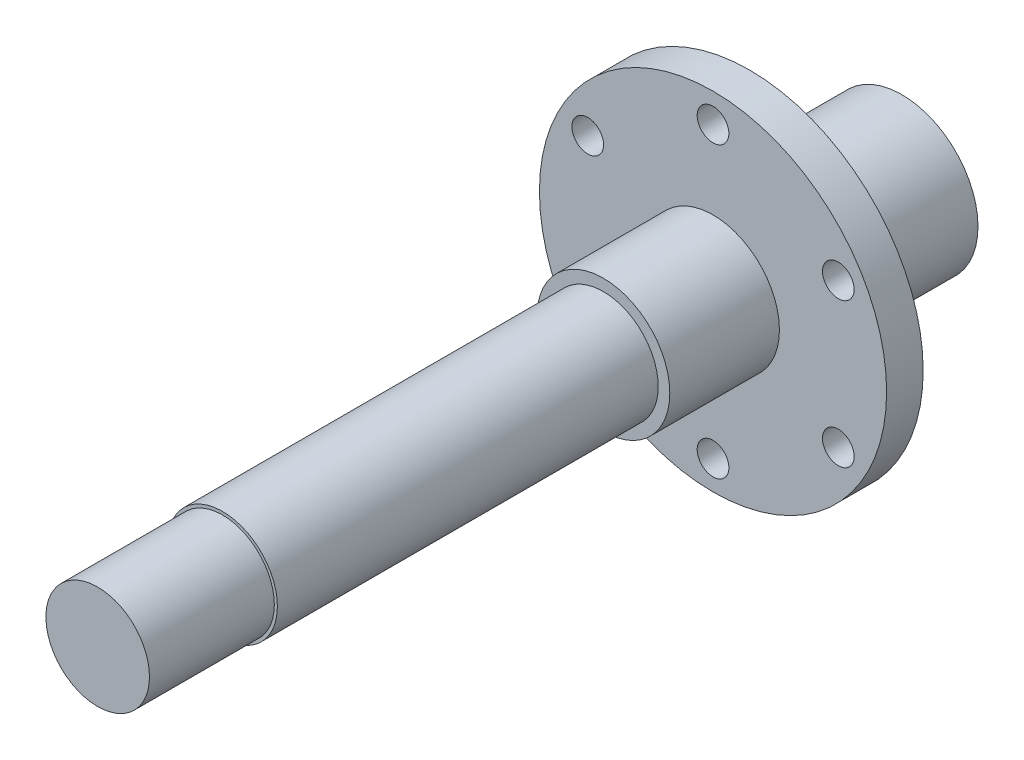
SolidWorks part; units mm, degrees
material "Galvanized Steel"
ref_plane "Front Plane" through (0, 0, 0) normal (0, 0, 1) x (1, 0, 0)
ref_plane "Top Plane" through (0, 0, 0) normal (0, 1, 0) x (1, 0, 0)
ref_plane "Right Plane" through (0, 0, 0) normal (1, 0, 0) x (0, 0, -1)
sketch "Sketch1" plane through (0, 0, 0) normal (0, 0, 1) x (1, 0, 0)
  circle A0 centre (0, 0) radius 12.5
  dimension "D1" = 25
extrude "Boss-Extrude1" add sketch "Sketch1" along normal blind 25
sketch "Sketch2" plane through (0, 0, 0) normal (0, 0, -1) x (-1, 0, 0)
  circle A0 centre (0, 0) radius 5
  dimension "D1" = 10
extrude "Cut-Extrude1" cut sketch "Sketch2" against normal blind 20
sketch "Sketch4" plane through (0, 0, 0) normal (0, 1, 0) x (1, 0, 0)
  line L0 (5, 0) -> (-5, 0) construction
  circle A0 centre (0, -8) radius 2
  dimension "D1" = 4
  dimension "D2" = 8
extrude "Cut-Extrude2" cut sketch "Sketch4" against normal blind 20
sketch "Sketch5" plane through (0, 0, 25) normal (0, 0, 1) x (1, 0, 0)
  circle A0 centre (0, 0) radius 28.5
  circle A1 centre (0, 0) radius 23.75 construction
  circle A2 centre (0, 23.75) radius 2.6
  circle A3 centre (20.5681, 11.875) radius 2.6
  circle A4 centre (20.5681, -11.875) radius 2.6
  circle A5 centre (0, -23.75) radius 2.6
  circle A6 centre (-20.5681, -11.875) radius 2.6
  circle A7 centre (-20.5681, 11.875) radius 2.6
  dimension "D1" = 57
  dimension "D2" = 5.2
  dimension "D3" = 47.5
  dimension "D4" = 6
extrude "Boss-Extrude2" add sketch "Sketch5" along normal blind 6
sketch "Sketch6" plane through (0, 0, 31) normal (0, 0, 1) x (1, 0, 0)
  circle A0 centre (0, 0) radius 9
  dimension "D1" = 18
extrude "Boss-Extrude3" add sketch "Sketch6" along normal blind 80.52
sketch "Sketch7" plane through (0, 0, 111.52) normal (0, 0, 1) x (1, 0, 0)
  circle A0 centre (0, 0) radius 8.5
  dimension "D1" = 17
extrude "Boss-Extrude4" add sketch "Sketch7" along normal blind 20.5
sketch "Sketch8" plane through (0, 0, 31) normal (0, 0, 1) x (1, 0, 0)
  circle A0 centre (0, 0) radius 10.9
  dimension "D1" = 21.8
extrude "Boss-Extrude5" add sketch "Sketch8" along normal blind 18
